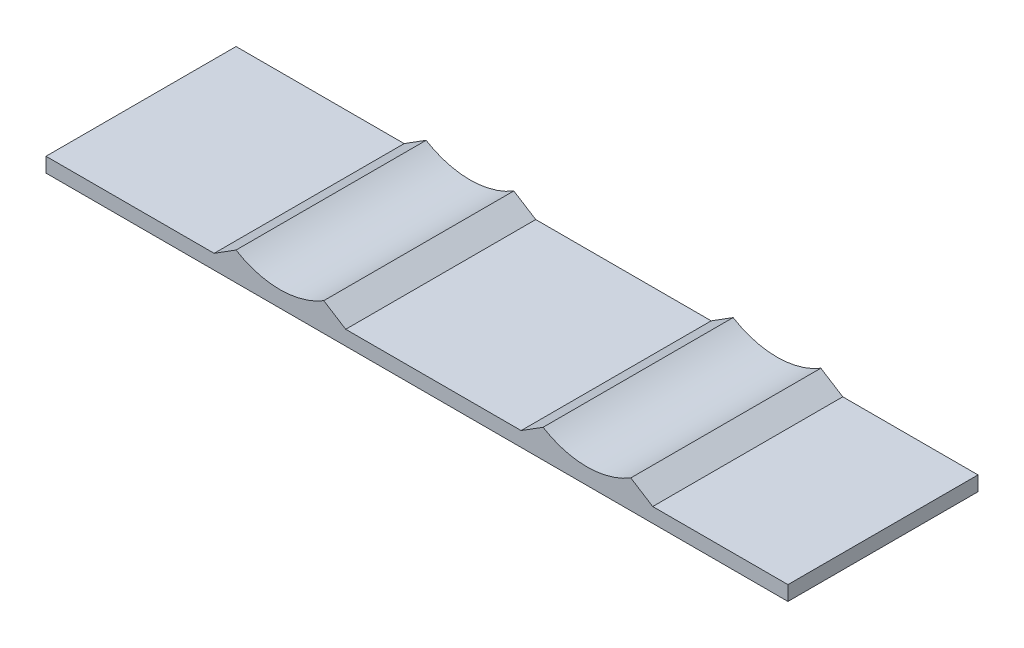
SolidWorks part; units mm, degrees
ref_plane "Front Plane" through (0, 0, 0) normal (0, 0, 1) x (1, 0, 0)
ref_plane "Top Plane" through (0, 0, 0) normal (0, 1, 0) x (1, 0, 0)
ref_plane "Right Plane" through (0, 0, 0) normal (1, 0, 0) x (0, 0, -1)
sketch "Sketch1" plane through (0, 0, 0) normal (0, 0, 1) x (1, 0, 0)
  line L0 (0, 0) -> (101.5, 0)
  line L1 (101.5, 0) -> (101.5, 2)
  line L2 (101.5, 2) -> (83, 2)
  line L3 (0, 2) -> (0, 0)
  line L4 (32, 13.7) -> (74, 13.7) construction
  line L5 (26, 3.8893) -> (23, 2)
  line L6 (38, 3.8893) -> (41, 2)
  line L7 (68, 3.8893) -> (65, 2)
  line L8 (80, 3.8893) -> (83, 2)
  line L9 (23, 2) -> (0, 2)
  line L10 (65, 2) -> (41, 2)
  arc A0 (26, 3.8893) -> (38, 3.8893) centre (32, 13.7) ccw
  arc A1 (68, 3.8893) -> (80, 3.8893) centre (74, 13.7) ccw
  point P19 (68, 2)
  point P24 (26, 2)
  dimension "D3" = 23
  dimension "D1" = 2
  dimension "D2" = 27.5
  dimension "D4" = 42
  dimension "D5" = 32
  dimension "D6" = 11.7
extrude "Boss-Extrude1" add sketch "Sketch1" along normal blind 26
